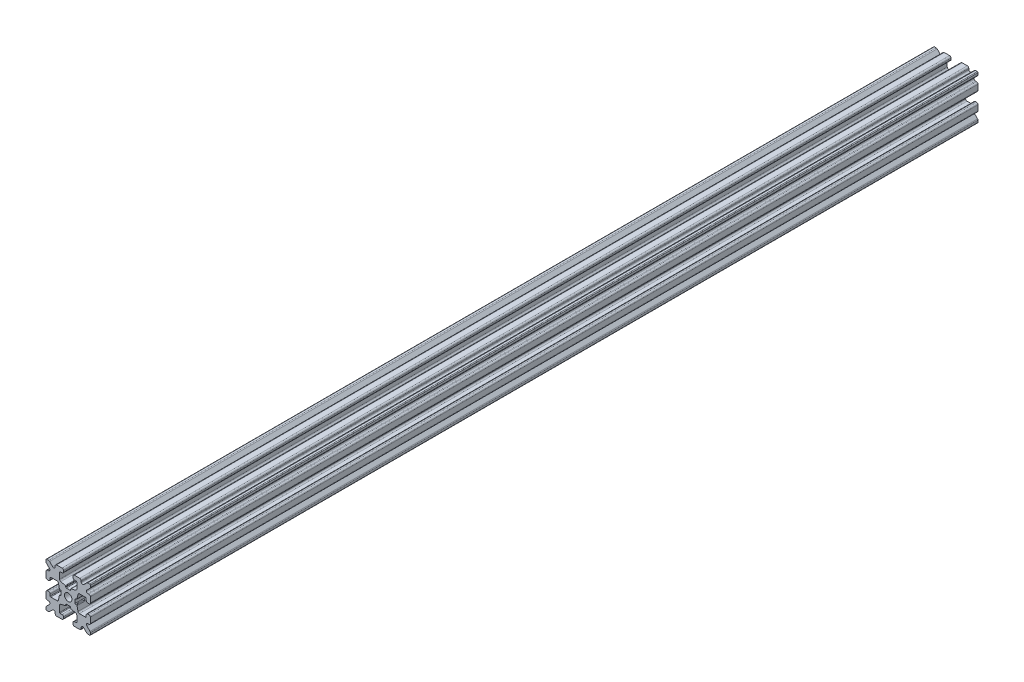
SolidWorks part; units mm, degrees
material "1060 Alloy"
ref_plane "Front Plane" through (0, 0, 0) normal (0, 0, 1) x (1, 0, 0)
ref_plane "Top Plane" through (0, 0, 0) normal (0, 1, 0) x (1, 0, 0)
ref_plane "Right Plane" through (0, 0, 0) normal (1, 0, 0) x (0, 0, -1)
sketch "Sketch1" plane through (0, 0, 0) normal (0, 0, 1) x (1, 0, 0)
  line L1 (-7.5, -7.5) -> (7.5, -7.5)
  line L2 (-7.5, -7.5) -> (-7.5, 7.5)
  line L3 (-7.5, 7.5) -> (7.5, 7.5)
  line L4 (7.5, -7.5) -> (7.5, 7.5)
  line L5 (-7.5, -7.5) -> (7.5, 7.5) construction
  line L6 (-7.5, 7.5) -> (7.5, -7.5) construction
  circle A0 centre (0, 0) radius 1.25
  point P0 (0, 0)
  dimension "D2" = 2.5
  dimension "D1" = 15
extrude "Boss-Extrude1" add sketch "Sketch1" along normal mid plane 300
fillet "Fillet1" radius 0.25 4 edges at (7.5, -7.5, 0) (-7.5, -7.5, 0) (7.5, 7.5, 0) (-7.5, 7.5, 0)
sketch "Sketch2" plane through (0, 0, 150) normal (0, 0, 1) x (1, 0, 0)
  line L0 (-7.5, 7.25) -> (-7.5, -7.25) construction
  line L1 (-7.5, 1.6) -> (-6.1, 1.6)
  line L2 (-7.5, 1.6) -> (-7.5, -1.6)
  line L3 (-7.5, -1.6) -> (-6.1, -1.6)
  line L4 (-6.1, 1.6) -> (-6.1, 2.9)
  line L5 (0, 0) -> (-12.1036, 0) construction
  line L6 (-6.1, -2.9) -> (-3.4, -2.9)
  line L7 (0, 0) -> (-7.25, 7.25) construction
  line L8 (-6.1, 2.9) -> (-3.4, 2.9)
  line L9 (-3.4, -2.9) -> (-3.4, 2.9)
  line L10 (55, 0) -> (-55, 0) construction
  line L11 (-6.1, -2.9) -> (-6.1, -1.6)
  line L12 (2.9, 6.1) -> (1.6, 6.1)
  line L13 (2.9, 3.4) -> (-2.9, 3.4)
  line L14 (-2.9, 6.1) -> (-2.9, 3.4)
  line L15 (2.9, 6.1) -> (2.9, 3.4)
  line L16 (-1.6, 6.1) -> (-2.9, 6.1)
  line L17 (1.6, 7.5) -> (1.6, 6.1)
  line L18 (-1.6, 7.5) -> (1.6, 7.5)
  line L19 (-1.6, 7.5) -> (-1.6, 6.1)
  line L20 (-1.6, -7.5) -> (-1.6, -6.1)
  line L21 (-1.6, -7.5) -> (1.6, -7.5)
  line L22 (1.6, -7.5) -> (1.6, -6.1)
  line L23 (-1.6, -6.1) -> (-2.9, -6.1)
  line L24 (2.9, -6.1) -> (2.9, -3.4)
  line L25 (-2.9, -6.1) -> (-2.9, -3.4)
  line L26 (2.9, -3.4) -> (-2.9, -3.4)
  line L27 (2.9, -6.1) -> (1.6, -6.1)
  line L28 (6.1, -2.9) -> (6.1, -1.6)
  line L29 (3.4, -2.9) -> (3.4, 2.9)
  line L30 (6.1, 2.9) -> (3.4, 2.9)
  line L31 (6.1, -2.9) -> (3.4, -2.9)
  line L32 (6.1, 1.6) -> (6.1, 2.9)
  line L33 (7.5, -1.6) -> (6.1, -1.6)
  line L34 (7.5, 1.6) -> (7.5, -1.6)
  line L35 (7.5, 1.6) -> (6.1, 1.6)
  dimension "D1" = 3.2
  dimension "D2" = 5.8
  dimension "D3" = 1.4
  dimension "D4" = 2.7
extrude "Cut-Extrude1" cut sketch "Sketch2" against normal through all
sketch "Sketch4" plane through (0, 0, 150) normal (0, 0, 1) x (1, 0, 0)
  line L0 (-3.4, 2.9) -> (-2.75, 0)
  line L1 (55, 0) -> (-55, 0) construction
  line L2 (-2.75, 0) -> (-3.4, -2.9)
  line L3 (-3.4, -2.9) -> (-3.4, 2.9) construction
  line L4 (-3.4, 2.9) -> (-3.4, -2.9)
  line L5 (-2.9, 3.4) -> (0, 2.75)
  line L6 (0, 2.75) -> (2.9, 3.4)
  line L7 (2.9, 3.4) -> (-2.9, 3.4)
  line L8 (3.4, 2.9) -> (2.75, 0)
  line L9 (2.75, 0) -> (3.4, -2.9)
  line L10 (3.4, -2.9) -> (3.4, 2.9)
  line L11 (-2.9, -3.4) -> (0, -2.75)
  line L12 (0, -2.75) -> (2.9, -3.4)
  line L13 (2.9, -3.4) -> (-2.9, -3.4)
  circle A2 centre (0, 0) radius 2.75
  circle A3 centre (0, 0) radius 2.75 construction
  dimension "D1" = 1.5
extrude "Cut-Extrude3" cut sketch "Sketch4" against normal through all
fillet "Fillet3" radius 0.5 16 edges at (-6.1, -1.6, 0) (-7.5, -1.6, 0) (-6.1, 1.6, 0) (-7.5, 1.6, 0) (-1.6, -7.5, 0) (-1.6, -6.1, 0) (1.6, -7.5, 0) (1.6, -6.1, 0) (6.1, -1.6, 0) (7.5, -1.6, 0) (7.5, 1.6, 0) (6.1, 1.6, 0) (1.6, 7.5, 0) (1.6, 6.1, 0) (-1.6, 7.5, 0) (-1.6, 6.1, 0)
fillet "Fillet4" radius 0.5 8 edges at (-3.4, 2.9, 0) (-3.4, -2.9, 0) (2.9, -3.4, 0) (-2.9, -3.4, 0) (3.4, -2.9, 0) (3.4, 2.9, 0) (-2.9, 3.4, 0) (2.9, 3.4, 0)
fillet "Fillet5" radius 3 4 edges at (0, -2.75, 0) (2.75, 0, 0) (-2.75, 0, 0) (0, 2.75, 0)
fillet "Fillet6" radius 0.2 8 edges at (-2.9, -6.1, 0) (2.9, -6.1, 0) (6.1, -2.9, 0) (6.1, 2.9, 0) (2.9, 6.1, 0) (-2.9, 6.1, 0) (-6.1, -2.9, 0) (-6.1, 2.9, 0)
sketch "Sketch5" plane through (0, 0, 150) normal (0, 0, 1) x (1, 0, 0)
  line L0 (0, 0) -> (-7.25, 7.25) construction
  line L1 (-7.5, 6.4393) -> (-5.4607, 4.4)
  line L2 (-6.4393, 7.5) -> (-4.4, 5.4607)
  line L3 (-7.5, 4.4) -> (-5.4607, 4.4)
  line L4 (-3.8003, 2.9) -> (-5.9, 2.9) construction
  line L5 (0, 0) -> (-12.1819, 0) construction
  line L6 (-4.4, 7.5) -> (-4.4, 5.4607)
  line L7 (-2.9, 5.9) -> (-2.9, 3.8003) construction
  line L8 (-7.5, 6.4393) -> (-7.5, 4.4)
  line L9 (-7.5, 7.25) -> (-7.5, 2.1) construction
  line L10 (2.1, -7.5) -> (7.25, -7.5) construction
  line L11 (7.5, -7.25) -> (7.5, -2.1) construction
  line L12 (7.25, 7.5) -> (2.1, 7.5) construction
  line L13 (-2.1, 7.5) -> (-7.25, 7.5) construction
  line L14 (-4.4, 7.5) -> (-6.4393, 7.5)
  line L16 (55, 0) -> (-55, 0) construction
  line L17 (0, 0) -> (0, 10.993) construction
  line L18 (0, -54.6431) -> (0, 54.6431) construction
  line L20 (4.4, 7.5) -> (6.4393, 7.5)
  line L22 (7.5, 6.4393) -> (7.5, 4.4)
  line L23 (4.4, 7.5) -> (4.4, 5.4607)
  line L24 (7.5, 4.4) -> (5.4607, 4.4)
  line L25 (6.4393, 7.5) -> (4.4, 5.4607)
  line L26 (7.5, 6.4393) -> (5.4607, 4.4)
  line L27 (7.5, -6.4393) -> (5.4607, -4.4)
  line L28 (6.4393, -7.5) -> (4.4, -5.4607)
  line L29 (7.5, -4.4) -> (5.4607, -4.4)
  line L30 (4.4, -7.5) -> (4.4, -5.4607)
  line L31 (7.5, -6.4393) -> (7.5, -4.4)
  line L33 (4.4, -7.5) -> (6.4393, -7.5)
  line L36 (-4.4, -7.5) -> (-6.4393, -7.5)
  line L38 (-7.5, -6.4393) -> (-7.5, -4.4)
  line L39 (-4.4, -7.5) -> (-4.4, -5.4607)
  line L40 (-7.5, -4.4) -> (-5.4607, -4.4)
  line L41 (-6.4393, -7.5) -> (-4.4, -5.4607)
  line L42 (-7.5, -6.4393) -> (-5.4607, -4.4)
  dimension "D1" = 1.5
  dimension "D2" = 1.5
  dimension "D3" = 1.5
extrude "Cut-Extrude4" cut sketch "Sketch5" against normal through all
fillet "Fillet8" radius 0.5 24 edges at (-5.4607, 4.4, 0) (-7.5, 4.4, 0) (-5.4607, -4.4, 0) (-7.5, -4.4, 0) (-4.4, -7.5, 0) (-4.4, -5.4607, 0) (4.4, -7.5, 0) (4.4, -5.4607, 0) (5.4607, -4.4, 0) (7.5, -4.4, 0) (7.5, 4.4, 0) (5.4607, 4.4, 0) (4.4, 5.4607, 0) (4.4, 7.5, 0) (-4.4, 5.4607, 0) (-4.4, 7.5, 0) (-6.4393, 7.5, 0) (-7.5, 6.4393, 0) (6.4393, 7.5, 0) (7.5, 6.4393, 0) (6.4393, -7.5, 0) (7.5, -6.4393, 0) (-6.4393, -7.5, 0) (-7.5, -6.4393, 0)
sketch "Sketch6" plane through (0, 0, 150) normal (0, 0, 1) x (1, 0, 0)
  line L0 (0, 0) -> (0, 11.013) construction
  line L1 (0.6561, 2.8971) -> (2.1235, 2.8971) construction
  line L2 (0, -54.6431) -> (0, 54.6431) construction
  line L3 (0, 0) -> (7.25, 7.25) construction
  line L4 (7.5, 0.8255) -> (7.5, -0.8255)
  line L5 (2.3471, 0.8255) -> (7.5, 0.8255)
  line L6 (0, 0) -> (12.4016, 0) construction
  line L7 (0.8255, -7.5) -> (-0.8255, -7.5)
  line L8 (2.3471, -0.8255) -> (2.3471, 0.8255)
  line L9 (0.8255, -2.3471) -> (0.8255, -7.5)
  line L10 (7.5, -0.8255) -> (2.3471, -0.8255)
  line L11 (-7.5, -0.8255) -> (-2.3471, -0.8255)
  line L12 (-2.3471, -0.8255) -> (-2.3471, 0.8255)
  line L13 (-0.8255, -2.3471) -> (0.8255, -2.3471)
  line L14 (-0.8255, 7.5) -> (-0.8255, 2.3471)
  line L15 (-0.8255, 2.3471) -> (0.8255, 2.3471)
  line L16 (-0.8255, -7.5) -> (-0.8255, -2.3471)
  line L17 (0.8255, 2.3471) -> (0.8255, 7.5)
  line L18 (0.8255, 7.5) -> (-0.8255, 7.5)
  line L19 (3.9, 7.5) -> (2.1, 7.5) construction
  line L20 (-2.3471, 0.8255) -> (-7.5, 0.8255)
  line L21 (-7.5, 0.8255) -> (-7.5, -0.8255)
  point P5 (0, -2.5973)
  point P7 (0, 2.5973)
  dimension "D3" = 0.55
  dimension "D1" = 1.651
extrude "Cut-Extrude5" cut sketch "Sketch6" against normal through all
fillet "Fillet10" radius 0.2 16 edges at (-2.935, 0.8255, 0) (-2.935, -0.8255, 0) (2.935, -0.8255, 0) (2.935, 0.8255, 0) (0.8255, 2.935, 0) (-0.8255, 2.935, 0) (-2.3471, 0.8255, 0) (-2.3471, -0.8255, 0) (0.8255, 2.3471, 0) (-0.8255, 2.3471, 0) (2.3471, 0.8255, 0) (2.3471, -0.8255, 0) (0.8255, -2.935, 0) (0.8255, -2.3471, 0) (-0.8255, -2.3471, 0) (-0.8255, -2.935, 0)
